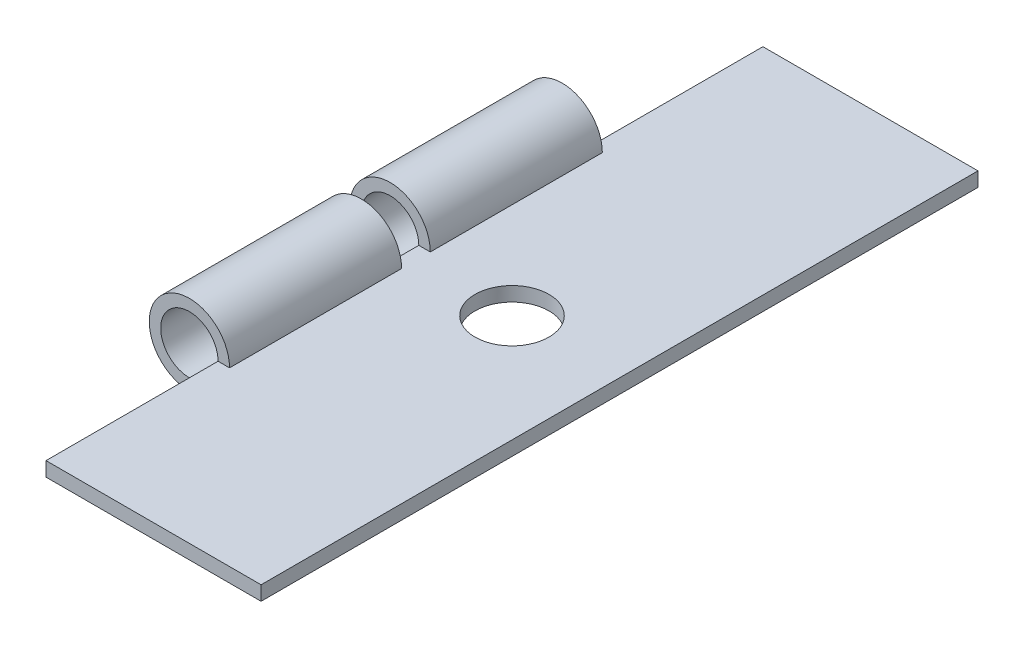
SolidWorks part; units mm, degrees
ref_plane "Front Plane" through (0, 0, 0) normal (0, 0, 1) x (1, 0, 0)
ref_plane "Top Plane" through (0, 0, 0) normal (0, 1, 0) x (1, 0, 0)
ref_plane "Right Plane" through (0, 0, 0) normal (1, 0, 0) x (0, 0, -1)
sketch "Sketch1" plane through (0, 0, 0) normal (0, 1, 0) x (1, 0, 0)
  line L1 (-4.7625, -15.875) -> (4.7625, -15.875)
  line L2 (-4.7625, -15.875) -> (-4.7625, 15.875)
  line L3 (-4.7625, 15.875) -> (4.7625, 15.875)
  line L4 (4.7625, -15.875) -> (4.7625, 15.875)
  line L5 (-4.7625, -15.875) -> (4.7625, 15.875) construction
  line L6 (-4.7625, 15.875) -> (4.7625, -15.875) construction
  point P0 (0, 0)
  dimension "D1" = 31.75
  dimension "D2" = 9.525
extrude "Boss-Extrude1" add sketch "Sketch1" along normal mid plane 0.635
sketch "Sketch5" plane through (0, 0.3175, 0) normal (0, 1, 0) x (1, 0, 0)
  line L0 (4.7625, 15.875) -> (-4.7625, 15.875) construction
  line L1 (-4.7625, 8.255) -> (-4.2545, 8.255)
  line L2 (-4.7625, 8.255) -> (-4.7625, 0.635)
  line L3 (-4.7625, 0.635) -> (-4.2545, 0.635)
  line L4 (-4.2545, 8.255) -> (-4.2545, 0.635)
  dimension "D1" = 0.508
  dimension "D2" = 7.62
  dimension "D3" = 7.62
ref_plane "Plane1" through (-6.0325, 0, 0) normal (-1, 0, 0) x (0, 0, 1)
ref_axis "Axis1" through (-6.0325, 0.3175, -15.875) along (0, 0, 1)
revolve "Revolve3" add sketch "Sketch5" angle 360 about axis through (-6.0325, 0.3175, -15.875) along (0, 0, 1)
mirror "Mirror2" about plane through (0, 0, 0) normal (0, 0, 1) of "Revolve3"
sketch "Sketch6" plane through (0, 0.3175, 0) normal (0, 1, 0) x (1, 0, 0)
  circle A0 centre (0, 0) radius 1.6383
extrude "Cut-Extrude1" cut sketch "Sketch6" against normal blind 12.7
equation "\"Loop to edge\" = - 0.3"
equation "\"D3@Sketch5\"=\"Loop to edge\""
